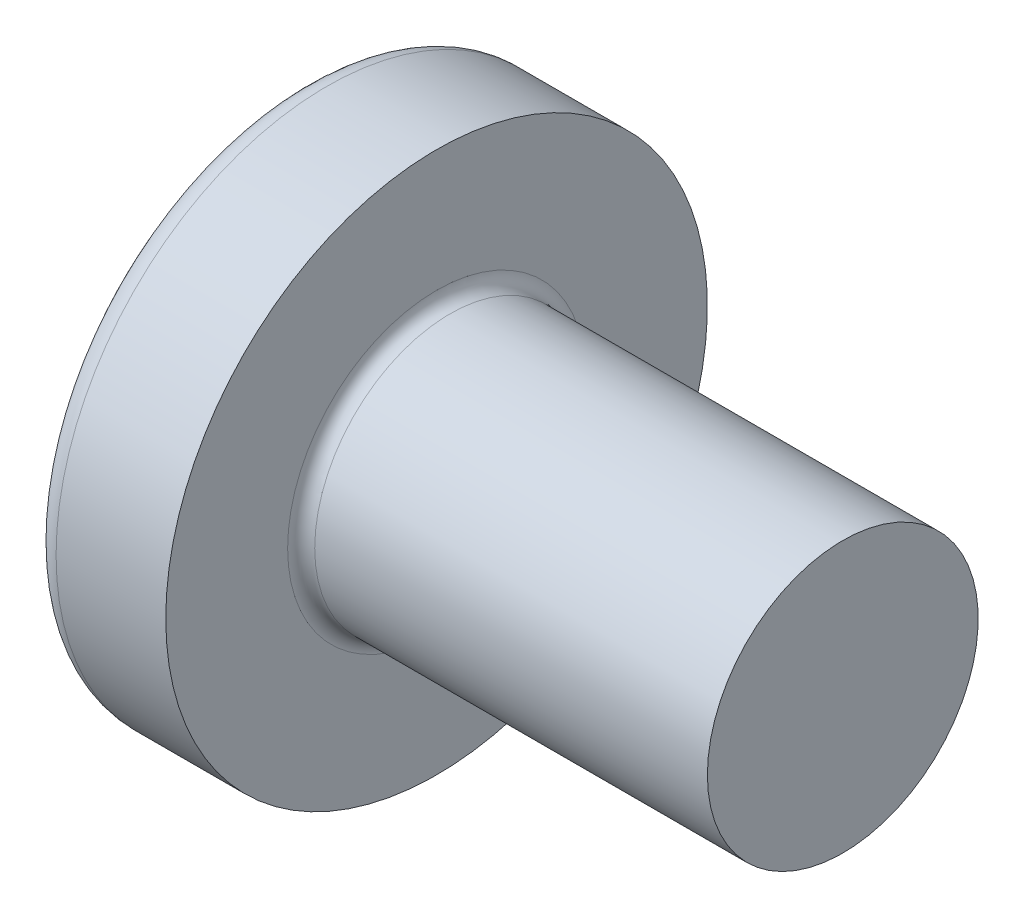
SolidWorks part; units mm, degrees
ref_plane "Plane1" through (0, 0, 0) normal (0, 0, 1) x (1, 0, 0)
ref_plane "Plane2" through (0, 0, 0) normal (0, 1, 0) x (1, 0, 0)
ref_plane "Plane3" through (0, 0, 0) normal (1, 0, 0) x (0, 0, -1)
sketch "BodySke" plane through (0, 0, 0) normal (0, 0, 1) x (1, 0, 0)
  line L0 (1.6, 1) -> (1.6, 2)
  line L1 (1.8, 6.35) -> (1.8, -3.175) construction
  line L2 (-25.4, 0) -> (127, 0) construction
  line L3 (4.6, 0) -> (0, 0)
  line L4 (1.6, 1) -> (4.6, 1)
  line L5 (4.6, 1) -> (4.6, 0)
  line L6 (0.79, 2) -> (1.6, 2)
  line L8 (1.6, 6.35) -> (1.6, -3.175) construction
  arc A0 (0.6464, 1.9285) -> (0, 0) centre (3.2, 0) ccw
  arc A2 (0.6464, 1.9285) -> (0.79, 2) centre (0.79, 1.82) cw
  dimension "Head_crown_rad" = 3.2
  dimension "Head_fillet_rad" = 0.18
  dimension "Length" = 3
  dimension "Head_ht" = 1.6
  dimension "Head_dia" = 4
  dimension "Advance" = 0.4
  dimension "Thread_nom" = 3
  dimension "Diameter" = 2
revolve "Base-Revolve" add sketch "BodySke"
cosmetic thread "ThreadCosmetic" [suppressed]
fillet "Fillet1" radius 0.1 1 edges at (1.6, 0, 1)
sketch "Sketch3" plane through (0, 0, 0) normal (1, 0, 0) x (0, 0, -1)
  line L0 (0.24, -1.05) -> (-0.24, -1.05)
  line L1 (0.24, -1.05) -> (0.24, 1.05)
  line L2 (-0.24, 1.05) -> (0.24, 1.05)
  line L3 (-0.24, 1.05) -> (-0.24, -1.05)
  dimension "Cross_dia" = 2.1
  dimension "D1" = 1.05
  dimension "Cross_width" = 0.48
  dimension "D2" = 0.24
ref_plane "Plane4" through (1.42, 0, 0) normal (1, 0, 0) x (0, 0, -1)
sketch "Sketch4" plane through (1.42, 0, 0) normal (1, 0, 0) x (0, 0, -1)
  line L0 (0.24, -0.342) -> (-0.24, -0.342)
  line L1 (0.24, -0.342) -> (0.24, 0.342)
  line L2 (-0.24, 0.342) -> (0.24, 0.342)
  line L3 (-0.24, 0.342) -> (-0.24, -0.342)
  dimension "D1" = 0.48
  dimension "D2" = 0.684
  dimension "D3" = 0.24
  dimension "D4" = 0.342
loft "Recess" cut profiles "Sketch3", "Sketch4"
pattern_circular "RecPat" count 2 every 90 about axis through (0, 0, 0) along (1, 0, 0) of "Recess"
sketch "RecCorSke" plane through (0, 0, 0) normal (0, 0, 1) x (1, 0, 0)
  line L0 (-3.175, 0) -> (15.875, 0) construction
  line L1 (-25.4, 0) -> (127, 0) construction
  line L2 (0, 0) -> (0, 0.4548)
  line L3 (0, 0.4548) -> (1.42, 0.3555)
  line L4 (1.42, 0.3555) -> (1.5355, 0)
  line L5 (1.5355, 0) -> (0, 0)
  dimension "Diameter" = 0.711
  dimension "Depth" = 1.42
  dimension "Draft_angle" = 4
  dimension "Bottom_angle" = 18
revolve "RecessCore" cut sketch "RecCorSke" angle 360 about L0
sketch "ThdSchSke" plane through (0, 0, 0) normal (0, 0, 1) x (1, 0, 0)
  line L0 (2.4, -0.774) -> (2.2418, -1)
  line L1 (2.4, -0.774) -> (2.5582, -1)
  line L2 (2.5582, -1) -> (2.5582, -1.25)
  line L3 (-3.175, 0) -> (5.1513, 0) construction
  line L5 (2.5582, -1.25) -> (2.2418, -1.25)
  line L6 (2.2418, -1.25) -> (2.2418, -1)
  dimension "Diameter" = 2
  dimension "SideAngle" = 55
  dimension "VeeAngle" = 70
  dimension "Thread_minor" = 1.548
  dimension "Overcut" = 2.5
  dimension "Start" = 2.4
revolve "ThreadSchematic" [suppressed] cut sketch "ThdSchSke" angle 360 about L3
pattern_linear "ThdSchPat" [suppressed]
equation "\"D1@Sketch3\" = \"Cross_dia@Sketch3\" / 2"
equation "\"D2@Sketch3\" = \"Cross_width@Sketch3\" / 2"
equation "\"Depth@RecCorSke\" = \"Cross_depth@Plane4\""
equation "\"D1@Sketch4\" = \"Cross_width@Sketch3\""
equation "\"D2@Sketch4\" = \"Cross_dia@Sketch3\" - 2.0 * \"Cross_depth@Plane4\" * tan(26.5  * 0.017453292)"
equation "\"D3@Sketch4\" = \"D1@Sketch4\" / 2"
equation "\"D4@Sketch4\" = \"D2@Sketch4\" / 2"
equation "\"Thread_length@ThreadCosmetic\" = ((sgn( (\"Length@BodySke\" - \"Advance@BodySke\" * 2.0 ) - \"Thread_nom@BodySke\" )-1)*( (\"Length@BodySke\" - \"Advance@BodySke\" * 2.0 ) - \"Thread_nom@BodySke\" ))/-2+ \"Thread_nom@BodySke\""
equation "\"Thread_minor@ThdSchSke\" = \"Thread_minor@ThreadCosmetic\""
equation "\"Diameter@ThdSchSke\" = \"Diameter@BodySke\""
equation "\"Overcut@ThdSchSke\" = \"Diameter@BodySke\" * 1.25"
equation "\"Start@ThdSchSke\" = \"Head_ht@BodySke\" + \"Length@BodySke\" - \"Thread_length@ThreadCosmetic\"  '---Non-countersunk---"
equation "\"Num_threads@ThdSchPat\" = int( \"Thread_length@ThreadCosmetic\" / \"Advance@BodySke\" + 0.999 )  + 1"
equation "\"Advance@ThdSchPat\" = \"Thread_length@ThreadCosmetic\" /  (\"Num_threads@ThdSchPat\" - 1) 'relax it"
